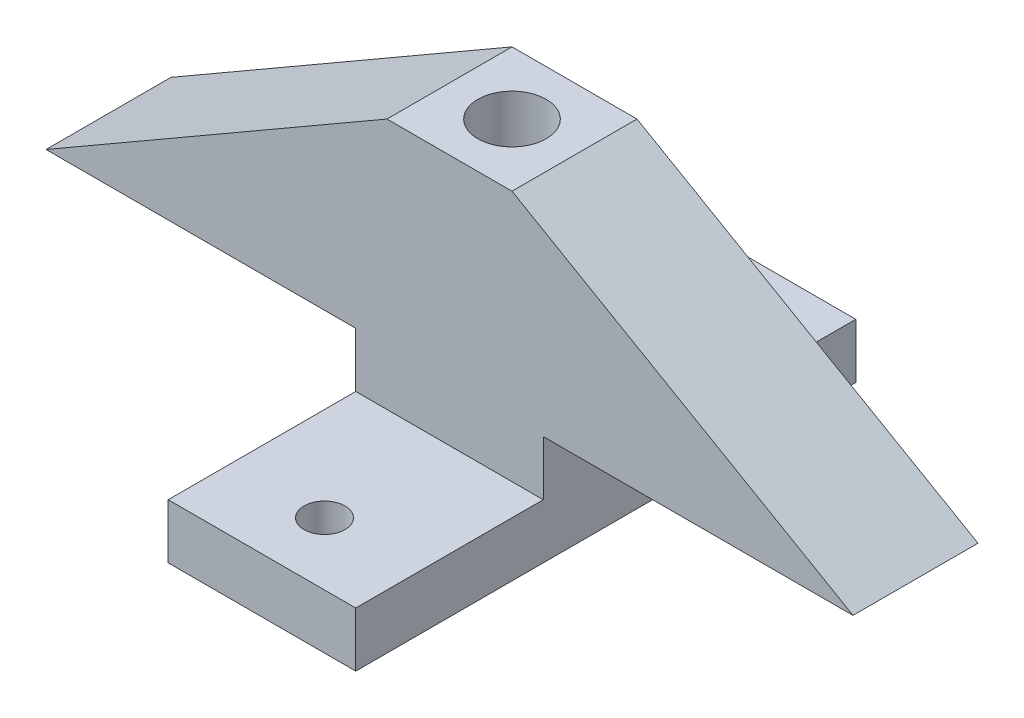
SolidWorks part; units mm, degrees
ref_plane "Front Plane" through (0, 0, 0) normal (0, 0, 1) x (1, 0, 0)
ref_plane "Top Plane" through (0, 0, 0) normal (0, 1, 0) x (1, 0, 0)
ref_plane "Right Plane" through (0, 0, 0) normal (1, 0, 0) x (0, 0, -1)
sketch "Sketch1" plane through (0, 0, 0) normal (0, 0, 1) x (1, 0, 0)
  line L0 (0, 0) -> (0, 22.225)
  line L1 (0, 22.225) -> (-62.932, 22.225)
  line L2 (-62.932, 22.225) -> (6.35, 62.225)
  line L3 (6.35, 62.225) -> (31.75, 62.225)
  line L4 (31.75, 62.225) -> (101.032, 22.225)
  line L5 (101.032, 22.225) -> (38.1, 22.225)
  line L6 (38.1, 22.225) -> (38.1, 0)
  line L7 (38.1, 0) -> (0, 0)
  point P9 (19.05, 62.225)
  point P10 (19.05, 0)
  dimension "D1" = 40
  dimension "D2" = 38.1
  dimension "D3" = 30
  dimension "D4" = 30
  dimension "D5" = 25.4
  dimension "D6" = 22.225
extrude "Boss-Extrude1" add sketch "Sketch1" along normal blind 25.4
sketch "Sketch2" plane through (0, 0, 25.4) normal (0, 0, 1) x (1, 0, 0)
  line L0 (38.1, 0) -> (38.1, 22.225) construction
  line L1 (0, 0) -> (38.1, 0)
  line L2 (0, 0) -> (0, 11.1125)
  line L3 (0, 11.1125) -> (38.1, 11.1125)
  line L4 (38.1, 0) -> (38.1, 11.1125)
extrude "Boss-Extrude2" add sketch "Sketch2" along normal blind 38.1
sketch "Sketch3" plane through (0, 0, 0) normal (0, 0, -1) x (-1, 0, 0)
  line L0 (0, 22.225) -> (0, 0) construction
  line L1 (-38.1, 0) -> (0, 0)
  line L2 (-38.1, 0) -> (-38.1, 11.1125)
  line L3 (-38.1, 11.1125) -> (0, 11.1125)
  line L4 (0, 0) -> (0, 11.1125)
extrude "Boss-Extrude3" add sketch "Sketch3" along normal blind 38.1
hole_wizard "Ø0.328in Dowel Hole1" positions "Sketch4" profile "Sketch5" hole size "Ø1.0" standard "ISO" end condition through all
sketch "Sketch4" plane through (0, 11.1125, 0) normal (0, 1, 0) x (1, 0, 0)
  point P0 (19.05, 25.4)
  point P2 (19.05, -50.8)
  dimension "D1" = 12.7
  dimension "D2" = 19.05
  dimension "D3" = 12.7
  dimension "D4" = 19.05
sketch "Sketch5" plane through (19.05, 11.1125, -25.4) normal (1, 0, 0) x (0, 0, 1)
  line L0 (0, 0) -> (0, 11.1125)
  line L1 (0, 11.1125) -> (4.1656, 11.1125)
  line L2 (4.1656, 11.1125) -> (4.1656, 0)
  line L5 (4.1656, 0) -> (0, 0)
  line L11 (0, -6.35) -> (0, 107.95) construction
  dimension "Thru Hole Dia." = 8.3312
  dimension "Thru Hole Depth" = 11.1125
hole_wizard "Ø0.55in Dowel Hole2" positions "Sketch7" profile "Sketch6" hole size "Ø1.0" standard "ISO"
sketch "Sketch7" plane through (0, 62.225, 0) normal (0, 1, 0) x (1, 0, 0)
  point P0 (19.05, -12.7)
  dimension "D1" = 12.7
  dimension "D2" = 12.7
sketch "Sketch6" plane through (19.05, 62.225, 12.7) normal (1, 0, 0) x (0, 0, 1)
  line L0 (0, 0) -> (0, 39.2261)
  line L1 (0, 39.2261) -> (6.9469, 35.052)
  line L2 (6.9469, 35.052) -> (6.9469, 0)
  line L5 (6.9469, 0) -> (0, 0)
  line L10 (0, 39.2261) -> (-6.9469, 35.052) construction
  line L11 (0, -6.35) -> (0, 107.95) construction
  dimension "Hole Dia." = 13.8938
  dimension "Hole Depth" = 35.052
  dimension "Drill Angle" = 118
